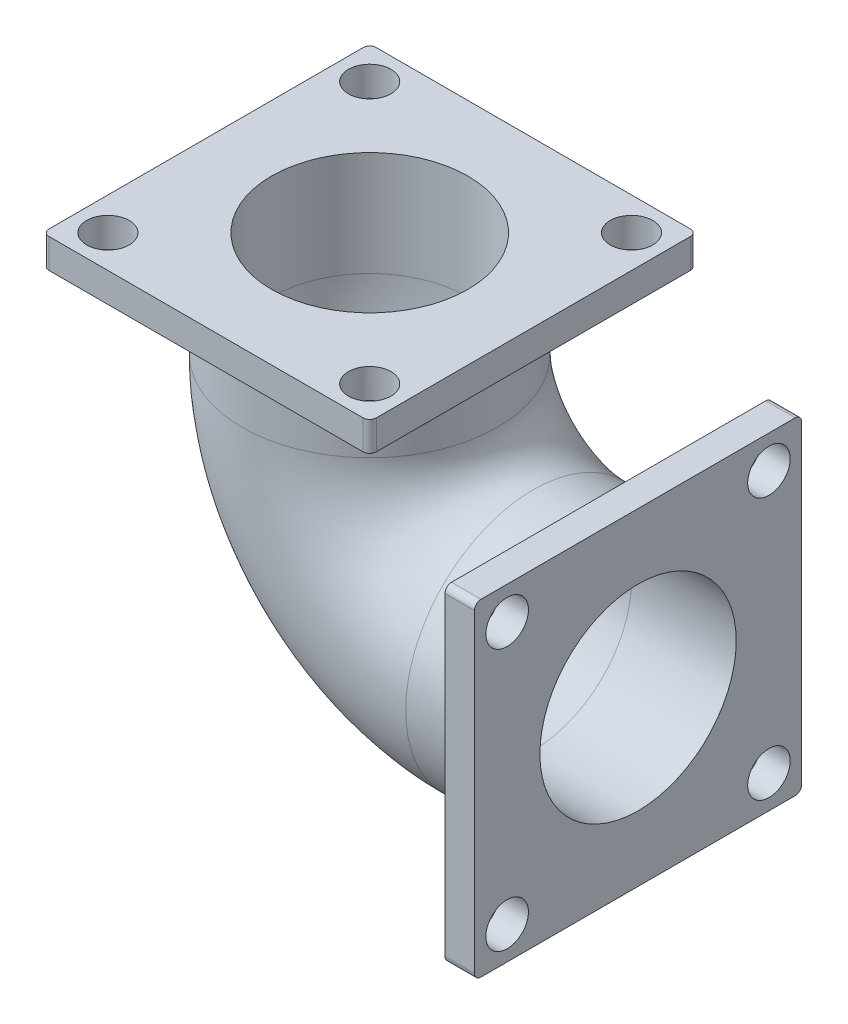
SolidWorks part; units mm, degrees
ref_plane "Front Plane" through (0, 0, 0) normal (0, 0, 1) x (1, 0, 0)
ref_plane "Top Plane" through (0, 0, 0) normal (0, 1, 0) x (1, 0, 0)
ref_plane "Right Plane" through (0, 0, 0) normal (1, 0, 0) x (0, 0, -1)
sketch "Sketch2" plane through (0, 0, 0) normal (0, 0, 1) x (1, 0, 0)
  line L0 (0, 0) -> (-160, 0)
  line L1 (-410, 250) -> (-410, 410)
  arc A0 (-160, 0) -> (-410, 250) centre (-160, 250) cw
  dimension "D3" = 250
  dimension "D1" = 160
sketch "Sketch3" plane through (0, 0, 0) normal (1, 0, 0) x (0, 0, -1)
  circle A0 centre (0, 0) radius 150
  dimension "D1" = 300
sweep "Sweep-Thin4" add profiles "Sketch3" path "Sketch2" parameters "D1"=45
sketch "Sketch8" plane through (0, 0, 0) normal (1, 0, 0) x (0, 0, -1)
  line L1 (-250, 250) -> (250, 250)
  line L2 (-250, 250) -> (-250, -250)
  line L3 (-250, -250) -> (250, -250)
  line L4 (250, 250) -> (250, -250)
  line L5 (-250, 250) -> (250, -250) construction
  line L6 (-250, -250) -> (250, 250) construction
  point P0 (0, 0)
  circle M6 centre (0, 0) radius 195
  dimension "D1" = 500
extrude "Boss-Extrude3" add sketch "Sketch8" against normal blind 45 contours L4 L1 L2 L3 M6
fillet "Fillet3" radius 10 4 edges at (-22.5, 250, -250) (-22.5, -250, 250) (-22.5, -250, -250) (-22.5, 250, 250)
sketch "Sketch9" plane through (0, 410, 0) normal (0, 1, 0) x (1, 0, 0)
  line L1 (-160, 250) -> (-660, 250)
  line L2 (-160, 250) -> (-160, -250)
  line L3 (-160, -250) -> (-660, -250)
  line L4 (-660, 250) -> (-660, -250)
  line L5 (-160, 250) -> (-660, -250) construction
  line L6 (-160, -250) -> (-660, 250) construction
  point P0 (-410, 0)
  circle M6 centre (-410, 0) radius 195
  dimension "D1" = 500
extrude "Boss-Extrude4" add sketch "Sketch9" against normal blind 45 contours L1 L4 L3 L2 M6
fillet "Fillet4" radius 10 4 edges at (-660, 387.5, 250) (-160, 387.5, 250) (-160, 387.5, -250) (-660, 387.5, -250)
sketch "Sketch10" plane through (0, 0, 0) normal (1, 0, 0) x (0, 0, -1)
  line L1 (-200, 200) -> (200, 200) construction
  line L2 (-200, 200) -> (-200, -200) construction
  line L3 (-200, -200) -> (200, -200) construction
  line L4 (200, 200) -> (200, -200) construction
  line L5 (-200, 200) -> (200, -200) construction
  line L6 (-200, -200) -> (200, 200) construction
  circle A0 centre (-200, 200) radius 32.5
  point P0 (0, 0)
  dimension "D2" = 65
  dimension "D1" = 400
extrude "Cut-Extrude2" cut sketch "Sketch10" against normal up to next
pattern_circular "CirPattern2" count 4 over 360 about axis through (0, 0, 0) along (1, 0, 0) of "Cut-Extrude2"
sketch "Sketch11" plane through (0, 410, 0) normal (0, 1, 0) x (1, 0, 0)
  line L1 (-210, 200) -> (-610, 200) construction
  line L2 (-210, 200) -> (-210, -200) construction
  line L3 (-210, -200) -> (-610, -200) construction
  line L4 (-610, 200) -> (-610, -200) construction
  line L5 (-210, 200) -> (-610, -200) construction
  line L6 (-210, -200) -> (-610, 200) construction
  circle A0 centre (-610, 200) radius 32.5
  point P0 (-410, 0)
  dimension "D2" = 65
  dimension "D1" = 400
extrude "Cut-Extrude3" cut sketch "Sketch11" against normal up to next
pattern_circular "CirPattern3" count 4 over 360 about axis through (-410, 0, 0) along (0, 1, 0) of "Cut-Extrude3"
